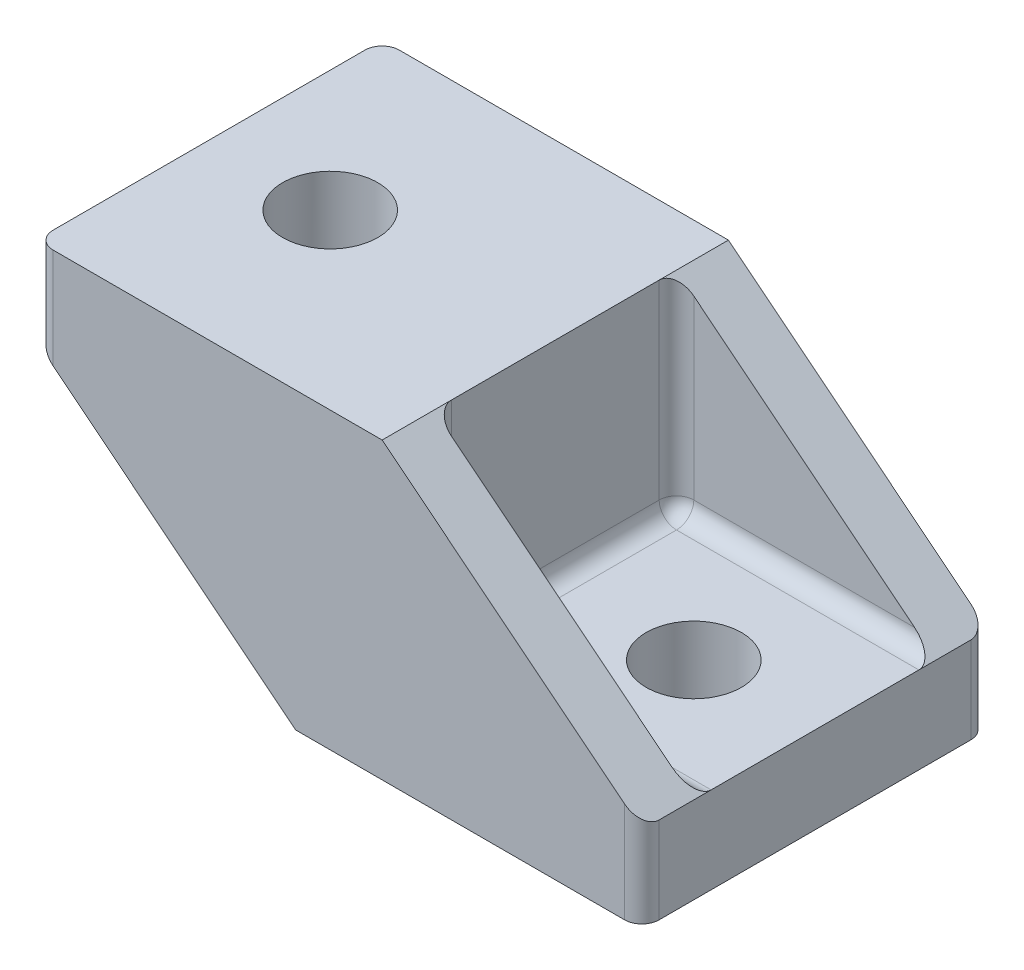
SolidWorks part; units mm, degrees
ref_plane "Front Plane" through (0, 0, 0) normal (0, 0, 1) x (1, 0, 0)
ref_plane "Top Plane" through (0, 0, 0) normal (0, 1, 0) x (1, 0, 0)
ref_plane "Right Plane" through (0, 0, 0) normal (1, 0, 0) x (0, 0, -1)
sketch "Sketch1" plane through (0, 0, 0) normal (0, 0, 1) x (1, 0, 0)
  line L0 (0, 0) -> (0, 12)
  line L1 (0, 12) -> (-15, 12)
  line L2 (-15, 12) -> (-15, 17)
  line L3 (-15, 17) -> (5, 17)
  line L4 (5, 17) -> (5, 5)
  line L5 (5, 5) -> (20, 5)
  line L6 (20, 5) -> (20, 0)
  line L7 (20, 0) -> (0, 0)
  point P5 (0, 0)
  dimension "D1" = 5
  dimension "D2" = 5
  dimension "D3" = 20
  dimension "D4" = 5
  dimension "D5" = 15
  dimension "D6" = 17
extrude "Boss-Extrude1" add sketch "Sketch1" along normal mid plane 20
sketch "Sketch2" plane through (0, 17, 0) normal (0, 1, 0) x (1, 0, 0)
  line L0 (-15, -10) -> (-15, 10) construction
  circle A0 centre (-8, 0) radius 2.75
  point P4 (0, 0)
  dimension "D1" = 5.5
  dimension "D2" = 7
extrude "Cut-Extrude1" cut sketch "Sketch2" against normal through all
sketch "Sketch3" plane through (0, 5, 0) normal (0, 1, 0) x (1, 0, 0)
  line L0 (20, -10) -> (20, 10) construction
  circle A0 centre (13, 0) radius 2.75
  point P4 (0, 0)
  dimension "D1" = 5.5
  dimension "D2" = 7
extrude "Cut-Extrude2" cut sketch "Sketch3" against normal through all
sketch "Sketch5" plane through (0, 0, -10) normal (0, 0, -1) x (-1, 0, 0)
  line L0 (-20, 5) -> (-5, 17)
  point P3 (0, 0)
rib "Rib7" sketch "Sketch5" sketch "Sketch5" thickness 3 extrusion direction parallel to sketch draft on no parameters "D1"=3
sketch "Sketch6" plane through (0, 0, -10) normal (0, 0, -1) x (-1, 0, 0)
  line L0 (15, 12) -> (0, 0)
  line L2 (0, 12) -> (0, 0) construction
  point P3 (0, 0)
  point P5 (0, 0)
rib "Rib8" sketch "Sketch6" sketch "Sketch6" thickness 3 extrusion direction parallel to sketch draft on no parameters "D1"=3
mirror "Mirror1" about plane through (0, 0, 0) normal (0, 0, 1) of "Rib8", "Rib7"
fillet "Fillet1" radius 1 10 edges at (5, 11, -7) (12.5, 5, -7) (12.5, 5, 7) (5, 11, 7) (5, 5, 0) (0, 12, 0) (0, 6, -7) (0, 6, 7) (-7.5, 12, 7) (-7.5, 12, -7)
fillet "Fillet2" radius 1 4 edges at (20, 2.5, -10) (20, 2.5, 10) (-15, 14.5, 10) (-15, 14.5, -10)
